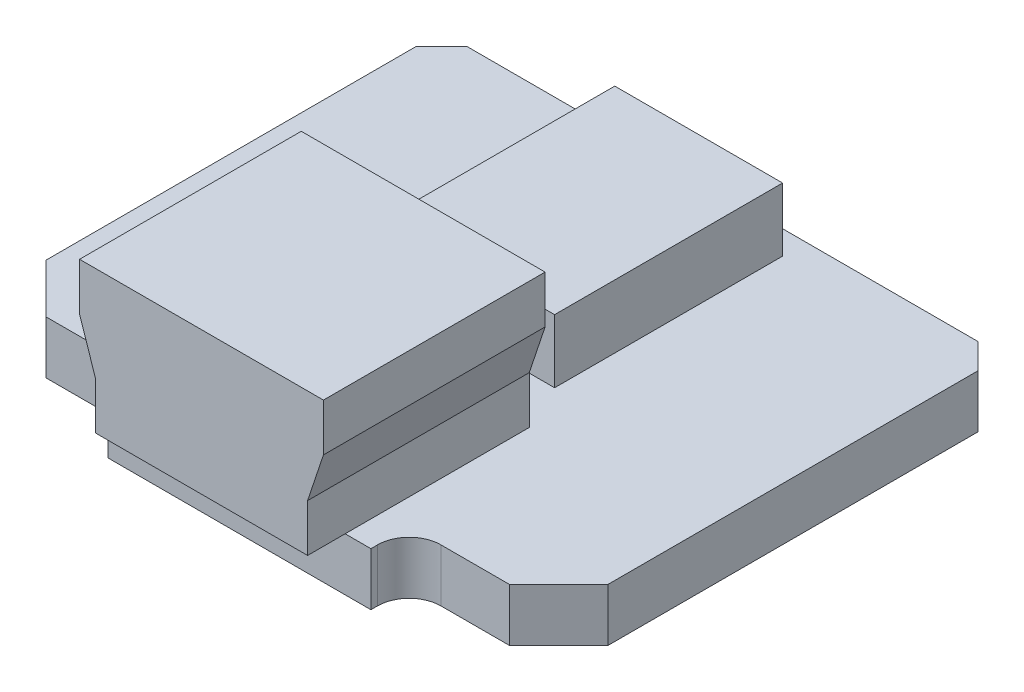
SolidWorks part; units mm, degrees
ref_plane "Front Plane" through (0, 0, 0) normal (0, 0, 1) x (1, 0, 0)
ref_plane "Top Plane" through (0, 0, 0) normal (0, 1, 0) x (1, 0, 0)
ref_plane "Right Plane" through (0, 0, 0) normal (1, 0, 0) x (0, 0, -1)
sketch "PCB Sketch" plane through (0, 0, 0) normal (0, 1, 0) x (1, 0, 0)
  line L0 (-8.07, 7.625) -> (8.07, 7.625)
  line L1 (8.87, 6.825) -> (8.87, -4.865)
  line L2 (7.32, -6.415) -> (5.15, -6.415)
  line L3 (4.15, -7.415) -> (4.15, -7.625)
  line L4 (4.15, -7.625) -> (-4.15, -7.625)
  line L5 (-4.15, -7.625) -> (-4.15, -7.415)
  line L6 (-5.15, -6.415) -> (-7.32, -6.415)
  line L7 (-8.87, -4.865) -> (-8.87, 6.825)
  line L8 (-8.87, 6.825) -> (-8.07, 7.625)
  line L9 (8.07, 7.625) -> (8.87, 6.825)
  line L10 (-7.32, -6.415) -> (-8.87, -4.865)
  line L11 (8.87, -4.865) -> (7.32, -6.415)
  line L12 (0, -7.625) -> (0, 7.625) construction
  arc A0 (-4.15, -7.415) -> (-5.15, -6.415) centre (-5.15, -7.415) ccw
  arc A1 (5.15, -6.415) -> (4.15, -7.415) centre (5.15, -7.415) ccw
  point P0 (-8.87, 7.625)
  point P1 (8.87, 7.625)
  point P3 (8.87, -6.415)
  point P8 (-8.87, -6.415)
  dimension "D5" = 1
  dimension "D6" = 1
  dimension "D1" = 17.74
  dimension "D2" = 14.04
  dimension "D3" = 8.3
  dimension "D4" = 15.25
extrude "PCB" add sketch "PCB Sketch" along normal blind 1.67
sketch "Sketch2" plane through (0, 1.67, 0) normal (0, 1, 0) x (1, 0, 0)
  line L0 (-2.65, 6.875) -> (2.65, 6.875)
  line L1 (2.65, 6.875) -> (2.65, -0.325)
  line L2 (2.65, -0.325) -> (-2.65, -0.325)
  line L3 (-2.65, -0.325) -> (-2.65, 6.875)
  line L6 (8.07, 7.625) -> (-8.07, 7.625) construction
  line L7 (-4.15, -7.625) -> (4.15, -7.625) construction
  point P7 (0, 6.875)
  point P8 (0, 7.625)
  dimension "D1" = 5.3
  dimension "D2" = 7.2
  dimension "D3" = 0
  dimension "D4" = 7.3
extrude "PIC18" add sketch "Sketch2" along normal blind 2
sketch "Sketch3" plane through (0, 0, 0) normal (0, -1, 0) x (1, 0, 0)
  line L0 (-6.04, 1.585) -> (-6.04, -4.795) construction
  line L1 (-3.81, 1.585) -> (-3.81, -4.795)
  line L2 (-8.27, 1.585) -> (-8.27, -4.795)
  line L3 (-8.87, -6.825) -> (-8.87, 4.865) construction
  line L4 (8.07, -7.625) -> (-8.07, -7.625) construction
  arc A0 (-3.81, 1.585) -> (-8.27, 1.585) centre (-6.04, 1.585) ccw
  arc A1 (-8.27, -4.795) -> (-3.81, -4.795) centre (-6.04, -4.795) ccw
  point P2 (-6.04, -1.605)
  point P9 (-6.04, -7.025)
  dimension "D1" = 0.6
  dimension "D2" = 0.6
extrude "Crystal" add sketch "Sketch3" along normal blind 0.72
sketch "Sketch5" plane through (0, -0.72, 0) normal (0, -1, 0) x (1, 0, 0)
  line L0 (-6.04, 1.585) -> (-6.04, -4.715) construction
  line L1 (-4.255, 1.585) -> (-4.255, -4.715)
  line L2 (-7.825, 1.585) -> (-7.825, -4.715)
  arc A0 (-4.255, 1.585) -> (-7.825, 1.585) centre (-6.04, 1.585) ccw
  arc A1 (-7.825, -4.715) -> (-4.255, -4.715) centre (-6.04, -4.715) ccw
  arc A2 (-8.27, -4.795) -> (-3.81, -4.795) centre (-6.04, -4.795) ccw construction
  point P2 (-6.04, -1.565)
  point P7 (-6.04, -6.5)
  point P8 (-6.04, -7.025)
  dimension "D1" = 0
  dimension "D2" = 0
extrude "Boss-Extrude4" add sketch "Sketch5" along normal blind 2.5
sketch3d "3DSketch1"
  line L0 (-3.8496, 6.1844, 1.825) -> (3.8504, 6.1844, 1.825)
  line L1 (3.8504, 6.1844, 1.825) -> (3.8504, 4.6844, 1.825)
  line L2 (3.8504, 4.6844, 1.825) -> (3.3504, 3.1844, 1.825)
  line L3 (3.3504, 3.1844, 1.825) -> (3.3504, 1.6844, 1.825)
  line L4 (3.3504, 1.6844, 1.825) -> (-3.3496, 1.6844, 1.825)
  line L6 (-3.3496, 3.1844, 1.825) -> (-3.3496, 1.6844, 1.825)
  line L7 (-3.8496, 4.6844, 1.825) -> (-3.3496, 3.1844, 1.825)
  line L8 (-3.8496, 6.1844, 1.825) -> (-3.8496, 4.6844, 1.825)
  dimension "D2" = 0.0144
  dimension "D5" = 1.5
  dimension "D6" = 1.5
  dimension "D1" = 1.5811
extrude "USB Connector" add sketch "3DSketch1" along direction (0, 0, -1) on the side of the normal blind 7 separate body
